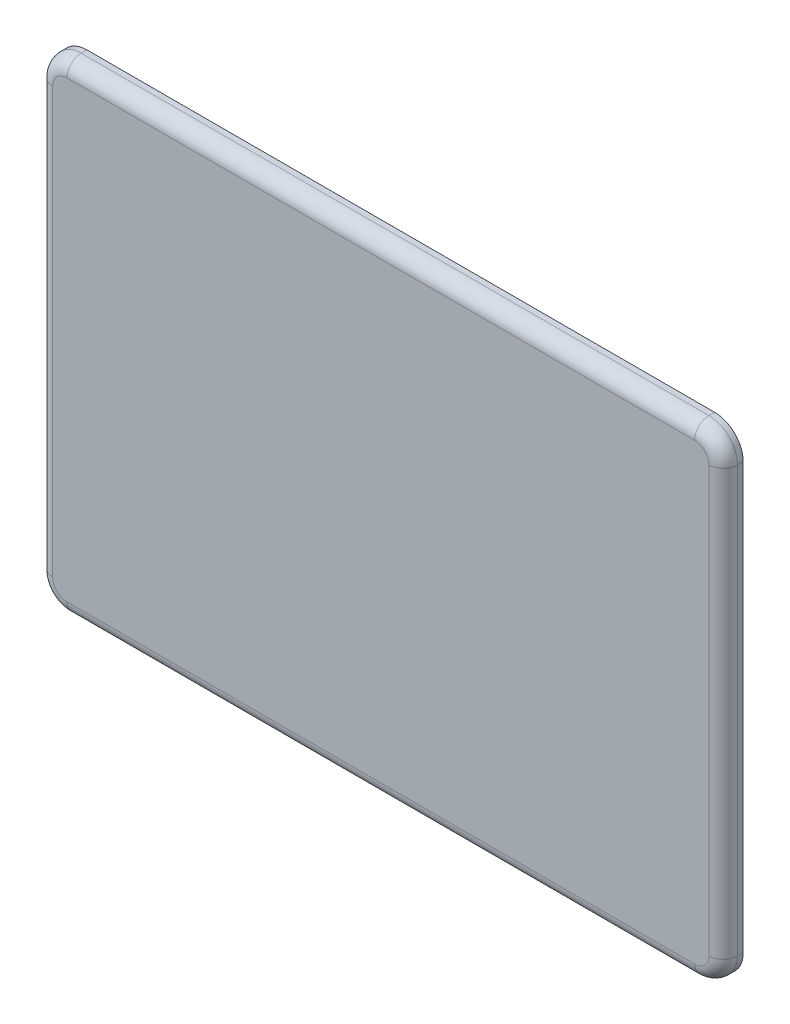
SolidWorks part; units mm, degrees
material "PTFE (general)"
ref_plane "Front Plane" through (0, 0, 0) normal (0, 0, 1) x (1, 0, 0)
ref_plane "Top Plane" through (0, 0, 0) normal (0, 1, 0) x (1, 0, 0)
ref_plane "Right Plane" through (0, 0, 0) normal (1, 0, 0) x (0, 0, -1)
sketch "Sketch1" plane through (0, 0, 0) normal (0, 0, 1) x (1, 0, 0)
  line L1 (-176.1179, 85.0737) -> (43.8821, 85.0737)
  line L2 (-186.1179, 75.0737) -> (-186.1179, -73.9263)
  line L3 (-176.1179, -83.9263) -> (43.8821, -83.9263)
  line L4 (53.8821, 75.0737) -> (53.8821, -73.9263)
  arc A0 (-176.1179, 85.0737) -> (-186.1179, 75.0737) centre (-176.1179, 75.0737) ccw
  arc A1 (-186.1179, -73.9263) -> (-176.1179, -83.9263) centre (-176.1179, -73.9263) ccw
  arc A2 (43.8821, -83.9263) -> (53.8821, -73.9263) centre (43.8821, -73.9263) ccw
  arc A3 (43.8821, 85.0737) -> (53.8821, 75.0737) centre (43.8821, 75.0737) cw
  point P6 (-186.1179, 85.0737)
  point P9 (-186.1179, -83.9263)
  point P14 (53.8821, 85.0737)
  dimension "D3" = 10
  dimension "D1" = 240
  dimension "D2" = 169
extrude "Boss-Extrude1" add sketch "Sketch1" along normal blind 7
fillet "Fillet2" radius 5 8 edges at (-183.189, 82.1448, 7) (-66.1179, 85.0737, 7) (50.9531, 82.1448, 7) (53.8821, 0.5737, 7) (50.9531, -80.9974, 7) (-66.1179, -83.9263, 7) (-183.189, -80.9974, 7) (-186.1179, 0.5737, 7)
ref_plane "Plane1" through (0, 0, 3.5) normal (0, 0, 1) x (1, 0, 0)
sketch "Sketch2" plane through (0, 0, 3.5) normal (0, 0, 1) x (1, 0, 0)
  line L1 (14.6561, 46.5359) -> (-155.6285, 46.5359)
  line L2 (14.6561, 46.5359) -> (14.6561, -60.3223)
  line L3 (14.6561, -60.3223) -> (-155.6285, -60.3223)
  line L4 (-155.6285, 46.5359) -> (-155.6285, -60.3223)
  point P4 (14.6561, 46.5359)
  point P5 (-155.6285, -60.3223)
extrude "Cut-Extrude1" cut sketch "Sketch2" against normal mid plane 4
